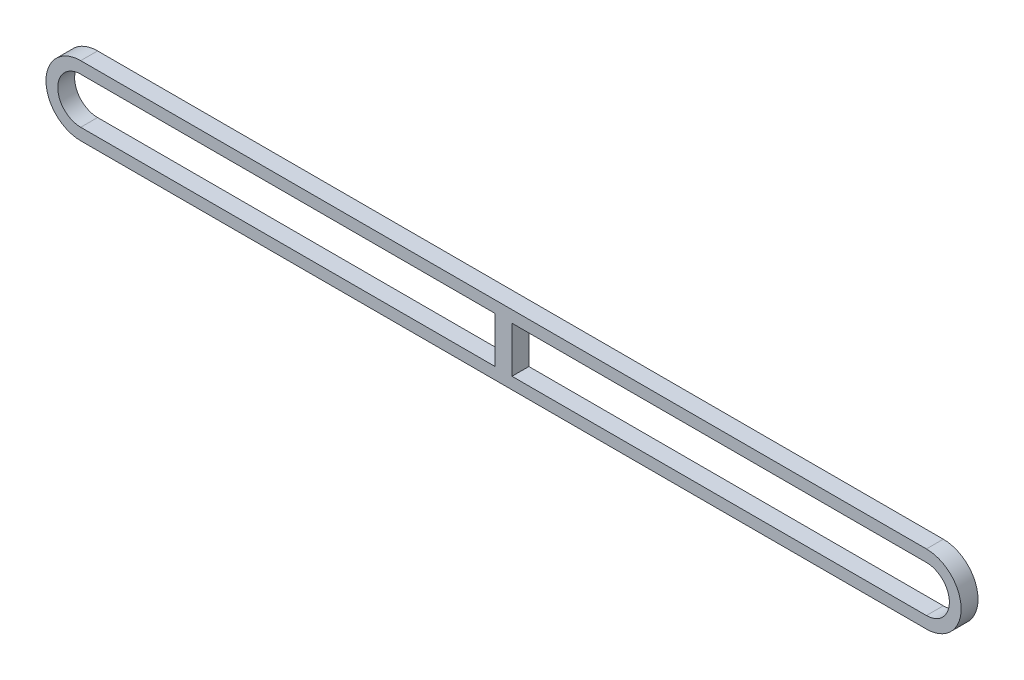
SolidWorks part; units mm, degrees
material "Custom Plastic"
ref_plane "Front Plane" through (0, 0, 0) normal (0, 0, 1) x (1, 0, 0)
ref_plane "Top Plane" through (0, 0, 0) normal (0, 1, 0) x (1, 0, 0)
ref_plane "Right Plane" through (0, 0, 0) normal (1, 0, 0) x (0, 0, -1)
sketch "Sketch1" plane through (0, 0, 0) normal (0, 0, 1) x (1, 0, 0)
  line L0 (0, 3.25) -> (119.637, 3.25)
  line L1 (0, -3.25) -> (119.637, -3.25)
  line L2 (0, 4.9109) -> (119.637, 4.9109)
  line L3 (0, -4.9109) -> (119.637, -4.9109)
  arc A0 (0, 3.25) -> (0, -3.25) centre (0, 0) ccw
  arc A1 (119.637, -3.25) -> (119.637, 3.25) centre (119.637, 0) ccw
  arc A2 (119.637, -4.9109) -> (119.637, 4.9109) centre (119.637, 0) ccw
  arc A3 (0, 4.9109) -> (0, -4.9109) centre (0, 0) ccw
  dimension "D1" = 6.5
  dimension "D2" = 119.637
  dimension "D3" = 1.6609
extrude "Boss-Extrude1" add sketch "Sketch1" against normal blind 2.3876
ref_plane "Plane1" through (59.8185, 0, 0) normal (1, 0, 0) x (0, 0, -1)
sketch "Sketch2" plane through (0, 0, 0) normal (0, 1, 0) x (1, 0, 0)
  line L0 (59.8185, -1.3132) -> (59.8185, 1.3132) construction
  line L1 (58.6247, 0) -> (61.0123, 0)
  line L2 (58.6247, 0) -> (58.6247, 2.3876)
  line L3 (58.6247, 2.3876) -> (61.0123, 2.3876)
  line L4 (61.0123, 0) -> (61.0123, 2.3876)
  line L5 (58.6247, 0) -> (61.0123, 2.3876) construction
  line L6 (58.6247, 2.3876) -> (61.0123, 0) construction
  line L7 (119.637, 2.3876) -> (0, 2.3876) construction
  line L8 (119.637, 0) -> (0, 0) construction
  point P0 (59.8185, 1.1938)
  dimension "D1" = 2.3876
extrude "Boss-Extrude2" add sketch "Sketch2" along normal up to next and the other way up to next contours L1 L4 L3 L2
